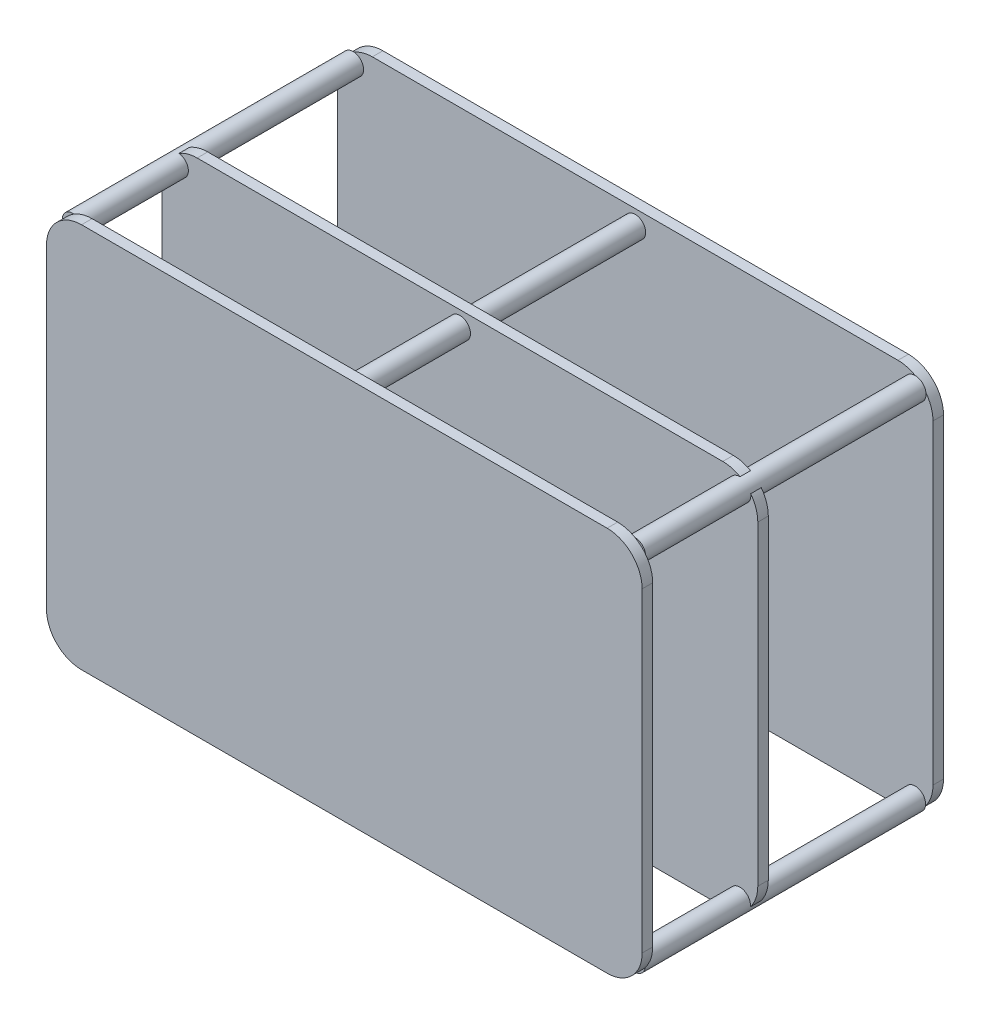
SolidWorks part; units mm, degrees
ref_plane "Front Plane" through (0, 0, 0) normal (0, 0, 1) x (1, 0, 0)
ref_plane "Top Plane" through (0, 0, 0) normal (0, 1, 0) x (1, 0, 0)
ref_plane "Right Plane" through (0, 0, 0) normal (1, 0, 0) x (0, 0, -1)
sketch "Sketch1" plane through (0, 0, 0) normal (0, 0, 1) x (1, 0, 0)
  line L1 (-75, 55) -> (75, 55)
  line L2 (-85, 45) -> (-85, -45)
  line L3 (-75, -55) -> (75, -55)
  line L4 (85, 45) -> (85, -45)
  line L5 (-85, 55) -> (85, -55) construction
  line L6 (-85, -55) -> (85, 55) construction
  arc A0 (-85, -45) -> (-75, -55) centre (-75, -45) ccw
  arc A1 (75, -55) -> (85, -45) centre (75, -45) ccw
  arc A2 (75, 55) -> (85, 45) centre (75, 45) cw
  arc A3 (-75, 55) -> (-85, 45) centre (-75, 45) ccw
  point P0 (0, 0)
  point P6 (4.315, 71.4771)
  point P11 (37.1162, 87.3881)
  dimension "D1" = 10
extrude "Bot plate" add sketch "Sketch1" along normal blind 3 contours L2 A0 L3 A1 L4 A2 L1 A3
sketch "Sketch2" plane through (0, 0, 3) normal (0, 0, 1) x (1, 0, 0)
  circle A0 centre (79.9027, 50.5759) radius 3.1173
  circle A1 centre (0, -50.7689) radius 3
  circle A2 centre (-80.5117, 50.5759) radius 3
  circle A3 centre (0, 50.5759) radius 3
  circle A4 centre (79.9027, -50.7689) radius 3
  circle A5 centre (-80.5117, -50.7689) radius 3
extrude "Standoffs" add sketch "Sketch2" along normal blind 50
sketch "Sketch15" plane through (0, 0, 53) normal (0, 0, 1) x (1, 0, 0)
  line L4 (75, 55) -> (-75, 55)
  line L5 (85, -45) -> (85, 45)
  line L6 (-75, -55) -> (75, -55)
  line L7 (-85, 45) -> (-85, -45)
  line L8 (75, 55) -> (-75, 55)
  line L9 (85, -45) -> (85, 45)
  line L10 (-75, -55) -> (75, -55)
  line L11 (-85, 45) -> (-85, -45)
  circle A1 centre (0, 50.5759) radius 3
  circle A2 centre (0, 50.5759) radius 3
  arc A6 (85, 45) -> (75, 55) centre (75, 45) ccw
  arc A7 (75, -55) -> (85, -45) centre (75, -45) ccw
  arc A8 (-85, -45) -> (-75, -55) centre (-75, -45) ccw
  arc A9 (-75, 55) -> (-85, 45) centre (-75, 45) ccw
  arc A10 (85, 45) -> (75, 55) centre (75, 45) ccw
  arc A11 (75, -55) -> (85, -45) centre (75, -45) ccw
  arc A12 (-85, -45) -> (-75, -55) centre (-75, -45) ccw
  arc A13 (-75, 55) -> (-85, 45) centre (-75, 45) ccw
  dimension "D1" = 0
  dimension "D2" = 0
extrude "top plate" add sketch "Sketch15" against normal blind 3
sketch "Sketch17" plane through (0, 0, 53) normal (0, 0, 1) x (1, 0, 0)
  circle A0 centre (-80.5117, -50.7689) radius 3
  circle A1 centre (-80.5117, 50.5759) radius 3
  circle A2 centre (0, 50.5759) radius 3
  circle A3 centre (79.9027, 50.5759) radius 3.1173
  circle A4 centre (79.9027, -50.7689) radius 3
  circle A6 centre (0, -50.7689) radius 3
extrude "Boss-Extrude2" add sketch "Sketch17" along normal blind 30
sketch "Sketch18" plane through (0, 0, 83) normal (0, 0, 1) x (1, 0, 0)
  line L1 (-75, -55) -> (75, -55)
  line L2 (-85, -45) -> (-85, 45)
  line L3 (-75, 55) -> (75, 55)
  line L4 (85, -45) -> (85, 45)
  line L5 (-85, -55) -> (85, 55) construction
  line L6 (-85, 55) -> (85, -55) construction
  arc A0 (-75, -55) -> (-85, -45) centre (-75, -45) cw
  arc A1 (75, 55) -> (85, 45) centre (75, 45) cw
  arc A2 (75, -55) -> (85, -45) centre (75, -45) ccw
  arc A3 (-85, 45) -> (-75, 55) centre (-75, 45) cw
  point P0 (0, 0)
  point P6 (0, 0)
  point P7 (0, 0)
  point P8 (0, 0)
  dimension "D1" = 10
  dimension "D2" = 10
extrude "Boss-Extrude3" add sketch "Sketch18" along normal blind 3 separate body
